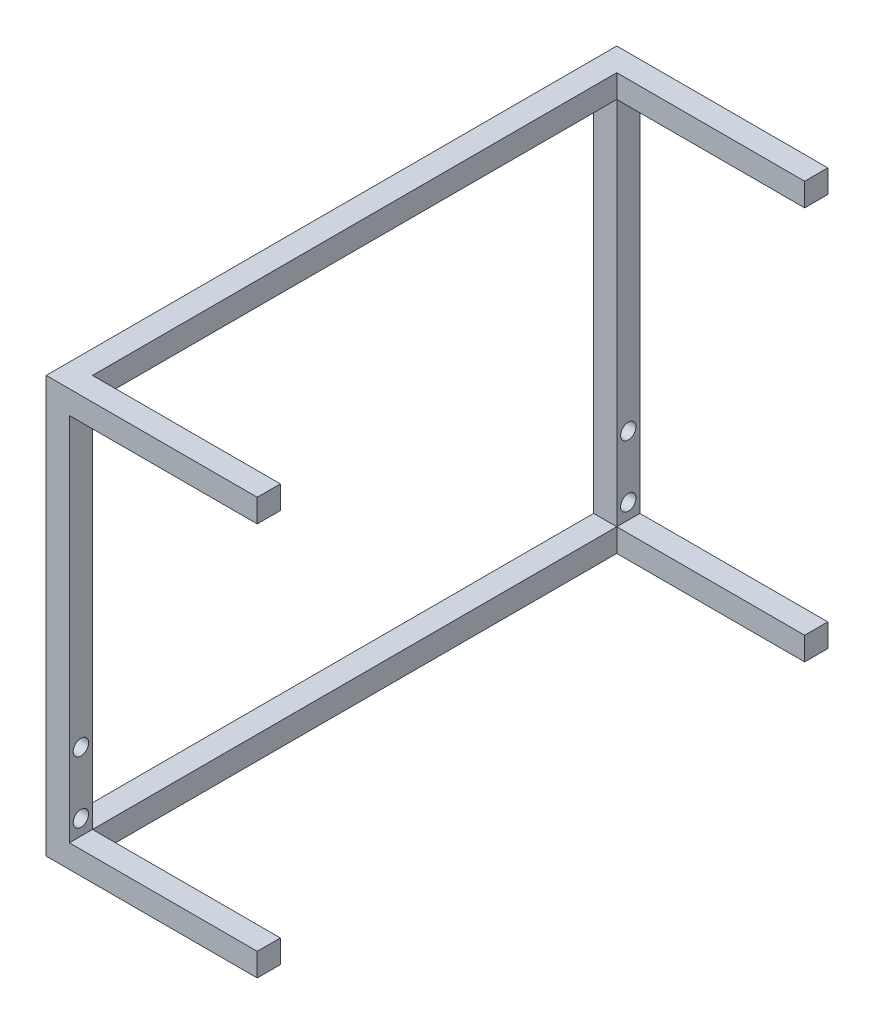
SolidWorks part; units mm, degrees
ref_plane "Front Plane" through (0, 0, 0) normal (0, 0, 1) x (1, 0, 0)
ref_plane "Top Plane" through (0, 0, 0) normal (0, 1, 0) x (1, 0, 0)
ref_plane "Right Plane" through (0, 0, 0) normal (1, 0, 0) x (0, 0, -1)
sketch "Sketch1" plane through (0, 0, 0) normal (1, 0, 0) x (0, 0, -1)
  line B0 (266.3935, -47.9263) -> (266.3935, 21.9237)
  line B1 (190.1935, -47.9263) -> (266.3935, -47.9263)
  line B2 (171.7484, -39.9888) -> (-140.6114, -39.9888)
  line B3 (-235.2565, -47.9263) -> (-159.0565, -47.9263)
  line B4 (-235.2565, 21.9237) -> (-235.2565, -47.9263)
  line B5 (247.3435, 40.9737) -> (-216.2065, 40.9737)
  circle B6 centre (-127.3065, 25.0987) radius 4.7625
  circle B7 centre (-127.3065, 25.0987) radius 6.35
  circle B8 centre (-32.0565, 25.0987) radius 4.7625
  circle B9 centre (-32.0565, 25.0987) radius 6.35
  circle B10 centre (158.4435, 25.0987) radius 4.7625
  circle B11 centre (63.1935, 25.0987) radius 6.35
  circle B12 centre (63.1935, 25.0987) radius 4.7625
  circle B13 centre (158.4435, 25.0987) radius 6.35
  arc B14 (266.3935, 21.9237) -> (247.3435, 40.9737) centre (247.3435, 21.9237) ccw
  arc B15 (-216.2065, 40.9737) -> (-235.2565, 21.9237) centre (-216.2065, 21.9237) ccw
sketch_block_instance "Block1-1"
sketch_block "Block1"
sketch "Sketch2" plane through (0, 0, 0) normal (1, 0, 0) x (0, 0, -1)
  line L0 (-235.2565, 15.5737) -> (-209.8565, 15.5737) construction
  line L1 (-219.3815, 275.9237) -> (-200.3315, 275.9237)
  line L2 (-219.3815, 275.9237) -> (-219.3815, -66.9763)
  line L3 (-219.3815, -66.9763) -> (-200.3315, -66.9763)
  line L4 (-200.3315, 275.9237) -> (-200.3315, -66.9763)
  line L6 (-200.3315, -47.9263) -> (231.4685, -47.9263)
  line L7 (-200.3315, -47.9263) -> (-200.3315, -66.9763)
  line L8 (-200.3315, -66.9763) -> (231.4685, -66.9763)
  line L14 (231.4685, -66.9763) -> (250.5185, -66.9763)
  line L15 (231.4685, -66.9763) -> (231.4685, 275.9237)
  line L16 (231.4685, 275.9237) -> (250.5185, 275.9237)
  line L17 (250.5185, -66.9763) -> (250.5185, 275.9237)
  line L18 (-200.3315, 275.9237) -> (231.4685, 275.9237)
  line L19 (-200.3315, 275.9237) -> (-200.3315, 256.8737)
  line L20 (-200.3315, 256.8737) -> (231.4685, 256.8737)
  line L21 (231.4685, 275.9237) -> (231.4685, 256.8737)
  line L23 (-235.2565, -1076.6263) -> (-161.0532, -1076.6263) construction
  line L24 (-235.2565, 21.9237) -> (-235.2565, -47.9263) construction
  line L26 (-209.8565, 40.9737) -> (-209.8565, 15.5737) construction
  line L27 (247.3435, 40.9737) -> (-216.2065, 40.9737) construction
  line L28 (-209.8565, 15.5737) -> (-209.8565, -47.9263) construction
  line L29 (-235.2565, -35.2263) -> (-209.8565, -35.2263) construction
  line L30 (-235.2565, -47.9263) -> (-159.0565, -47.9263) construction
  line L31 (240.9935, 40.9737) -> (240.9935, -47.9263) construction
  line L32 (266.3935, -47.9263) -> (266.3935, 21.9237) construction
  line L33 (240.9935, 15.5737) -> (266.3935, 15.5737) construction
  line L34 (240.9935, -35.2263) -> (266.3935, -35.2263) construction
  line L35 (231.4685, -47.9263) -> (231.4685, -66.9763)
  dimension "D1" = 19.05
  dimension "D2" = 19.05
  dimension "D3" = 19.05
  dimension "D4" = 19.05
  dimension "D5" = 304.8
  dimension "D6" = 25.4
  dimension "D7" = 25.4
  dimension "D8" = 50.8
  dimension "D9" = 25.4
extrude "Boss-Extrude1" add sketch "Sketch2" along normal blind 19.05
sketch "Sketch3" plane through (19.05, 0, 0) normal (1, 0, 0) x (0, 0, -1)
  circle A0 centre (-209.8565, 15.5737) radius 6.35
  circle A1 centre (-209.8565, -35.2263) radius 6.35
  circle A3 centre (240.9935, -35.2263) radius 6.35
  circle A4 centre (240.9935, 15.5737) radius 6.35
  dimension "D1" = 12.7
  dimension "D2" = 12.7
  dimension "D3" = 12.7
  dimension "D4" = 12.7
extrude "Cut-Extrude1" cut sketch "Sketch3" against normal blind 25.4
sketch "Sketch4" plane through (19.05, 0, 0) normal (1, 0, 0) x (0, 0, -1)
  line L1 (-219.3815, -66.9763) -> (-200.3315, -66.9763)
  line L2 (-219.3815, -66.9763) -> (-219.3815, -47.9263)
  line L3 (-219.3815, -47.9263) -> (-200.3315, -47.9263)
  line L4 (-200.3315, -66.9763) -> (-200.3315, -47.9263)
  line L5 (-219.3815, 275.9237) -> (-200.3315, 275.9237)
  line L6 (-219.3815, 275.9237) -> (-219.3815, 256.8737)
  line L7 (-219.3815, 256.8737) -> (-200.3315, 256.8737)
  line L8 (-200.3315, 275.9237) -> (-200.3315, 256.8737)
  line L9 (250.5185, 275.9237) -> (231.4685, 275.9237)
  line L10 (250.5185, 275.9237) -> (250.5185, 256.8737)
  line L11 (250.5185, 256.8737) -> (231.4685, 256.8737)
  line L12 (231.4685, 275.9237) -> (231.4685, 256.8737)
  line L13 (231.4685, -47.9263) -> (250.5185, -47.9263)
  line L14 (231.4685, -47.9263) -> (231.4685, -66.9763)
  line L15 (231.4685, -66.9763) -> (250.5185, -66.9763)
  line L16 (250.5185, -47.9263) -> (250.5185, -66.9763)
extrude "Boss-Extrude2" add sketch "Sketch4" along normal blind 154.7495
